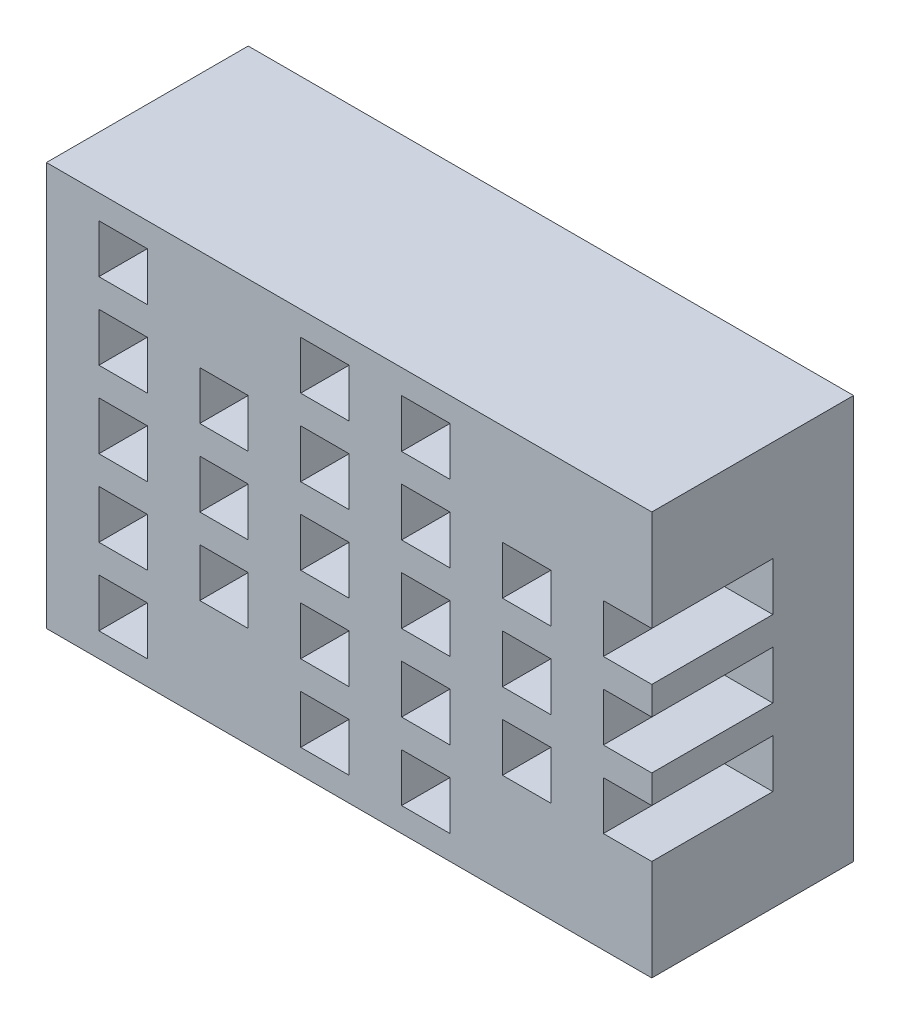
SolidWorks part; units mm, degrees
ref_plane "前视基准面" through (0, 0, 0) normal (0, 0, 1) x (1, 0, 0)
ref_plane "上视基准面" through (0, 0, 0) normal (0, 1, 0) x (1, 0, 0)
ref_plane "右视基准面" through (0, 0, 0) normal (1, 0, 0) x (0, 0, -1)
other "Configuration Table"
sketch "草图1" plane through (0, 0, 0) normal (0, 0, 1) x (1, 0, 0)
  line L1 (0, 0) -> (15, 0)
  line L2 (0, 0) -> (0, -10)
  line L3 (0, -10) -> (15, -10)
  line L4 (15, 0) -> (15, -10)
  dimension "D1" = 15
  dimension "D2" = 10
extrude "凸台-拉伸1" add sketch "草图1" along normal blind 5
sketch "草图2" plane through (0, 0, 5) normal (0, 0, 1) x (1, 0, 0)
  line L0 (15, -10) -> (15, 0) construction
  line L1 (1.3, -0.6) -> (2.5, -0.6)
  line L2 (1.3, -0.6) -> (1.3, -1.8)
  line L3 (1.3, -1.8) -> (2.5, -1.8)
  line L4 (2.5, -0.6) -> (2.5, -1.8)
  line L5 (1.3, -2.5) -> (2.5, -2.5)
  line L6 (1.3, -2.5) -> (1.3, -3.7)
  line L7 (1.3, -3.7) -> (2.5, -3.7)
  line L8 (2.5, -2.5) -> (2.5, -3.7)
  line L9 (1.3, -4.4) -> (2.5, -4.4)
  line L10 (1.3, -4.4) -> (1.3, -5.6)
  line L11 (1.3, -5.6) -> (2.5, -5.6)
  line L12 (2.5, -4.4) -> (2.5, -5.6)
  line L13 (1.3, -6.3) -> (2.5, -6.3)
  line L14 (1.3, -6.3) -> (1.3, -7.5)
  line L15 (1.3, -7.5) -> (2.5, -7.5)
  line L16 (2.5, -6.3) -> (2.5, -7.5)
  line L17 (1.3, -8.2) -> (2.5, -8.2)
  line L18 (1.3, -8.2) -> (1.3, -9.4)
  line L19 (1.3, -9.4) -> (2.5, -9.4)
  line L20 (2.5, -8.2) -> (2.5, -9.4)
  line L21 (3.8, -2.5) -> (5, -2.5)
  line L22 (3.8, -2.5) -> (3.8, -3.7)
  line L23 (3.8, -3.7) -> (5, -3.7)
  line L24 (5, -2.5) -> (5, -3.7)
  line L25 (6.3, -2.5) -> (7.5, -2.5)
  line L26 (6.3, -2.5) -> (6.3, -3.7)
  line L27 (6.3, -3.7) -> (7.5, -3.7)
  line L28 (7.5, -2.5) -> (7.5, -3.7)
  line L29 (11.3, -2.5) -> (12.5, -2.5)
  line L30 (10, -3.7) -> (8.8, -3.7)
  line L31 (10, -3.7) -> (10, -2.5)
  line L32 (10, -2.5) -> (8.8, -2.5)
  line L33 (8.8, -3.7) -> (8.8, -2.5)
  line L34 (11.3, -2.5) -> (11.3, -3.7)
  line L35 (11.3, -3.7) -> (12.5, -3.7)
  line L36 (12.5, -2.5) -> (12.5, -3.7)
  line L37 (13.8, -2.5) -> (15, -2.5)
  line L38 (13.8, -2.5) -> (13.8, -3.7)
  line L39 (13.8, -3.7) -> (15, -3.7)
  line L40 (15, -2.5) -> (15, -3.7)
  line L41 (15, 0) -> (0, 0) construction
  line L42 (3.8, -4.4) -> (5, -4.4)
  line L43 (3.8, -4.4) -> (3.8, -5.6)
  line L44 (3.8, -5.6) -> (5, -5.6)
  line L45 (5, -4.4) -> (5, -5.6)
  line L46 (6.3, -4.4) -> (7.5, -4.4)
  line L47 (6.3, -4.4) -> (6.3, -5.6)
  line L48 (6.3, -5.6) -> (7.5, -5.6)
  line L49 (7.5, -4.4) -> (7.5, -5.6)
  line L50 (8.8, -4.4) -> (10, -4.4)
  line L51 (8.8, -4.4) -> (8.8, -5.6)
  line L52 (8.8, -5.6) -> (10, -5.6)
  line L53 (10, -4.4) -> (10, -5.6)
  line L54 (11.3, -4.4) -> (12.5, -4.4)
  line L55 (11.3, -4.4) -> (11.3, -5.6)
  line L56 (11.3, -5.6) -> (12.5, -5.6)
  line L57 (12.5, -4.4) -> (12.5, -5.6)
  line L58 (13.8, -4.4) -> (15, -4.4)
  line L59 (13.8, -4.4) -> (13.8, -5.6)
  line L60 (13.8, -5.6) -> (15, -5.6)
  line L61 (15, -4.4) -> (15, -5.6)
  line L62 (3.8, -6.3) -> (5, -6.3)
  line L63 (3.8, -6.3) -> (3.8, -7.5)
  line L64 (3.8, -7.5) -> (5, -7.5)
  line L65 (5, -6.3) -> (5, -7.5)
  line L66 (6.3, -6.3) -> (7.5, -6.3)
  line L67 (6.3, -6.3) -> (6.3, -7.5)
  line L68 (6.3, -7.5) -> (7.5, -7.5)
  line L69 (7.5, -6.3) -> (7.5, -7.5)
  line L70 (8.8, -6.3) -> (10, -6.3)
  line L71 (8.8, -6.3) -> (8.8, -7.5)
  line L72 (8.8, -7.5) -> (10, -7.5)
  line L73 (10, -6.3) -> (10, -7.5)
  line L74 (11.3, -6.3) -> (12.5, -6.3)
  line L75 (11.3, -6.3) -> (11.3, -7.5)
  line L76 (11.3, -7.5) -> (12.5, -7.5)
  line L77 (12.5, -6.3) -> (12.5, -7.5)
  line L78 (13.8, -6.3) -> (15, -6.3)
  line L79 (13.8, -6.3) -> (13.8, -7.5)
  line L80 (13.8, -7.5) -> (15, -7.5)
  line L81 (15, -6.3) -> (15, -7.5)
  line L82 (6.3, -8.2) -> (7.5, -8.2)
  line L83 (6.3, -8.2) -> (6.3, -9.4)
  line L84 (6.3, -9.4) -> (7.5, -9.4)
  line L85 (7.5, -8.2) -> (7.5, -9.4)
  line L86 (8.8, -8.2) -> (10, -8.2)
  line L87 (8.8, -8.2) -> (8.8, -9.4)
  line L88 (8.8, -9.4) -> (10, -9.4)
  line L89 (10, -8.2) -> (10, -9.4)
  line L90 (6.3, -0.6) -> (7.5, -0.6)
  line L91 (6.3, -0.6) -> (6.3, -1.8)
  line L92 (6.3, -1.8) -> (7.5, -1.8)
  line L93 (7.5, -0.6) -> (7.5, -1.8)
  line L95 (8.8, -0.6) -> (10, -0.6)
  line L96 (8.8, -0.6) -> (8.8, -1.8)
  line L97 (8.8, -1.8) -> (10, -1.8)
  line L98 (10, -0.6) -> (10, -1.8)
  point P96 (7.5, -3.1)
  dimension "D1" = 1.2
  dimension "D2" = 1.2
  dimension "D3" = 1.2
  dimension "D4" = 1.2
  dimension "D5" = 1.2
  dimension "D6" = 1.2
  dimension "D7" = 1.2
  dimension "D8" = 1.2
  dimension "D9" = 1.2
  dimension "D10" = 1.2
  dimension "D11" = 1.2
  dimension "D12" = 1.2
  dimension "D13" = 1.2
  dimension "D14" = 1.2
  dimension "D15" = 1.2
  dimension "D16" = 1.2
  dimension "D17" = 1.2
  dimension "D18" = 1.2
  dimension "D19" = 1.2
  dimension "D20" = 1.2
  dimension "D21" = 1.2
  dimension "D22" = 1.2
  dimension "D23" = 1.2
  dimension "D24" = 1.2
  dimension "D25" = 1.2
  dimension "D26" = 1.2
  dimension "D27" = 1.2
  dimension "D28" = 1.2
  dimension "D29" = 1.2
  dimension "D30" = 1.2
  dimension "D31" = 1.2
  dimension "D32" = 1.2
  dimension "D33" = 1.2
  dimension "D34" = 1.2
  dimension "D35" = 1.2
  dimension "D36" = 1.2
  dimension "D37" = 1.2
  dimension "D38" = 1.2
  dimension "D39" = 1.2
  dimension "D40" = 1.2
  dimension "D41" = 1.2
  dimension "D42" = 1.2
  dimension "D43" = 1.2
  dimension "D44" = 1.2
  dimension "D45" = 1.2
  dimension "D46" = 1.2
  dimension "D47" = 0.7
  dimension "D48" = 0.7
  dimension "D49" = 2.5
  dimension "D50" = 1.3
  dimension "D51" = 1.3
  dimension "D52" = 1.3
  dimension "D53" = 1.3
  dimension "D54" = 1.3
  dimension "D55" = 0.7
  dimension "D56" = 0.7
  dimension "D57" = 1.2
extrude "切除-拉伸1" cut sketch "草图2" against normal blind 3
